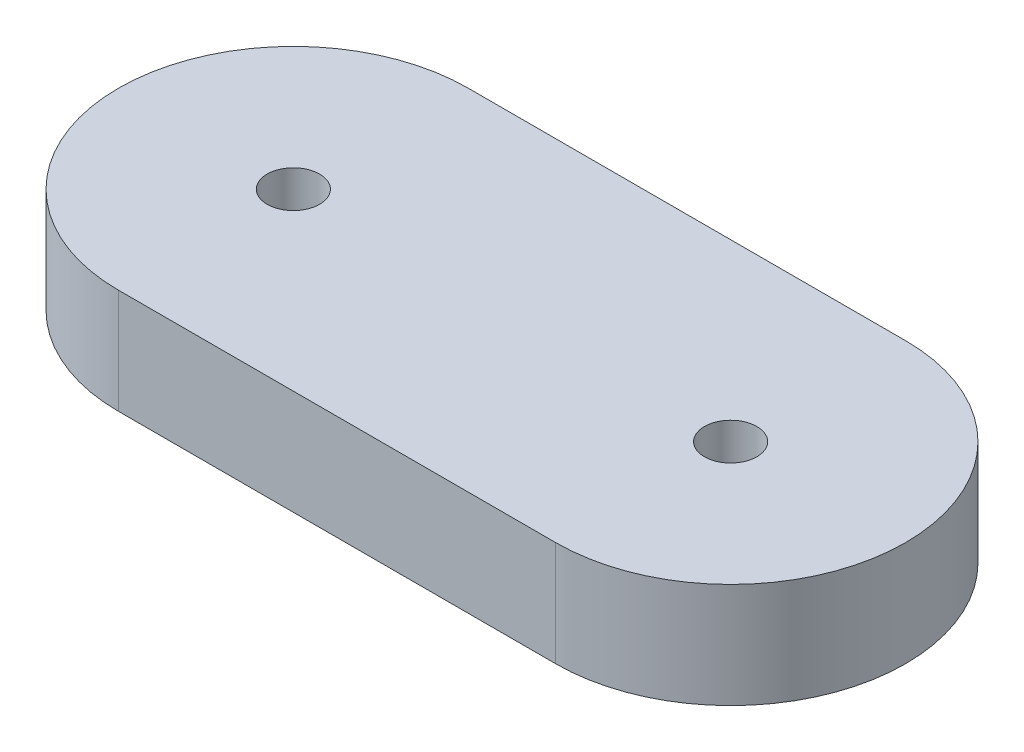
SolidWorks part; units mm, degrees
ref_plane "Front Plane" through (0, 0, 0) normal (0, 0, 1) x (1, 0, 0)
ref_plane "Top Plane" through (0, 0, 0) normal (0, 1, 0) x (1, 0, 0)
ref_plane "Right Plane" through (0, 0, 0) normal (1, 0, 0) x (0, 0, -1)
sketch "Sketch1" plane through (0, 0, 0) normal (0, 1, 0) x (1, 0, 0)
  line L0 (-12.5, 0) -> (12.5, 0) construction
  line L1 (-3.3, 0) -> (3.3, 0) construction
  line L2 (-12.5, 10) -> (0, 10)
  line L3 (-12.5, -10) -> (0, -10)
  line L4 (-11, 10) -> (-11, -10) construction
  line L5 (-6, 10) -> (-6, -10) construction
  line L6 (0, 10) -> (0, -10)
  line L9 (0, -6.6834) -> (0, 6.6834) construction
  arc A0 (-12.5, 10) -> (-12.5, -10) centre (-12.5, 0) ccw
  circle A3 centre (-12.5, 0) radius 1.5
  circle A4 centre (0, 0) radius 6 construction
  point P5 (0, 0)
  point P7 (0, 6)
  dimension "D1" = 3
  dimension "D2" = 12
  dimension "D3" = 5
  dimension "D4" = 4
extrude "Boss-Extrude1" add sketch "Sketch1" along normal blind 6
mirror "Mirror1" about plane through (0, 6, -10) normal (-1, 0, 0) of "Boss-Extrude1"
equation "\"M3_d\"= \"M3_d_laser@troublemaker.Assembly\""
equation "\"rod_z_d\"= 12"
equation "\"t\"=4"
equation "\"t2\"= 5"
equation "\"D1@Sketch1\"=\"M3_d\""
equation "\"D2@Sketch1\"=\"rod_z_d\""
equation "\"D4@Sketch1\"=\"t\""
equation "\"housing_t\"= \"housing_t_glob@troublemaker.Assembly\""
equation "\"D1@Boss-Extrude1\"=\"housing_t\""
